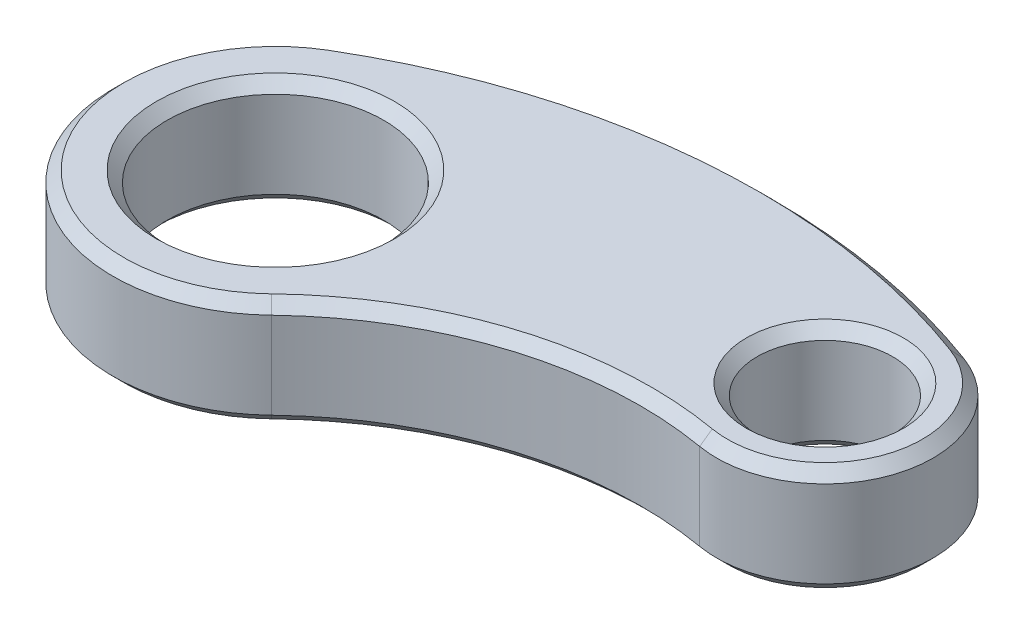
SolidWorks part; units mm, degrees
ref_plane "Alzado" through (0, 0, 0) normal (0, 0, 1) x (1, 0, 0)
ref_plane "Planta" through (0, 0, 0) normal (0, 1, 0) x (1, 0, 0)
ref_plane "Vista lateral" through (0, 0, 0) normal (1, 0, 0) x (0, 0, -1)
sketch "Croquis2" plane through (0, 0, 0) normal (0, 1, 0) x (1, 0, 0)
  line L0 (0, 0) -> (0, -38.6582) construction
  arc A0 (-15.2698, 25.8231) -> (20.8244, -21.595) centre (0, 0) ccw
  arc A1 (81.4078, -3.0184) -> (91.7831, 35.44) centre (84.8345, 16.6859) ccw
  arc A2 (91.7831, 35.44) -> (-15.2698, 25.8231) centre (48.3543, -81.7732) ccw
  arc A3 (81.4078, -3.0184) -> (20.8244, -21.595) centre (69.4147, -71.9833) ccw
  circle A4 centre (0, 0) radius 20
  circle A5 centre (84.8345, 16.6859) radius 12.5
extrude "Saliente-Extruir1" add sketch "Croquis2" along normal blind 20
chamfer "Chaflán1" distance 2 angle 45 12 edges at (0, 0, 20) (84.8345, 0, -4.1859) (48.8937, 0, 5.0588) (-23.8712, 0, 18.1705) (104.1441, 0, -11.4766) (37.1702, 0, -42.7254) (84.8345, 20, -4.1859) (0, 20, 20) (-23.8712, 20, 18.1705) (37.1702, 20, -42.7254) (104.1441, 20, -11.4766) (48.8937, 20, 5.0588)
